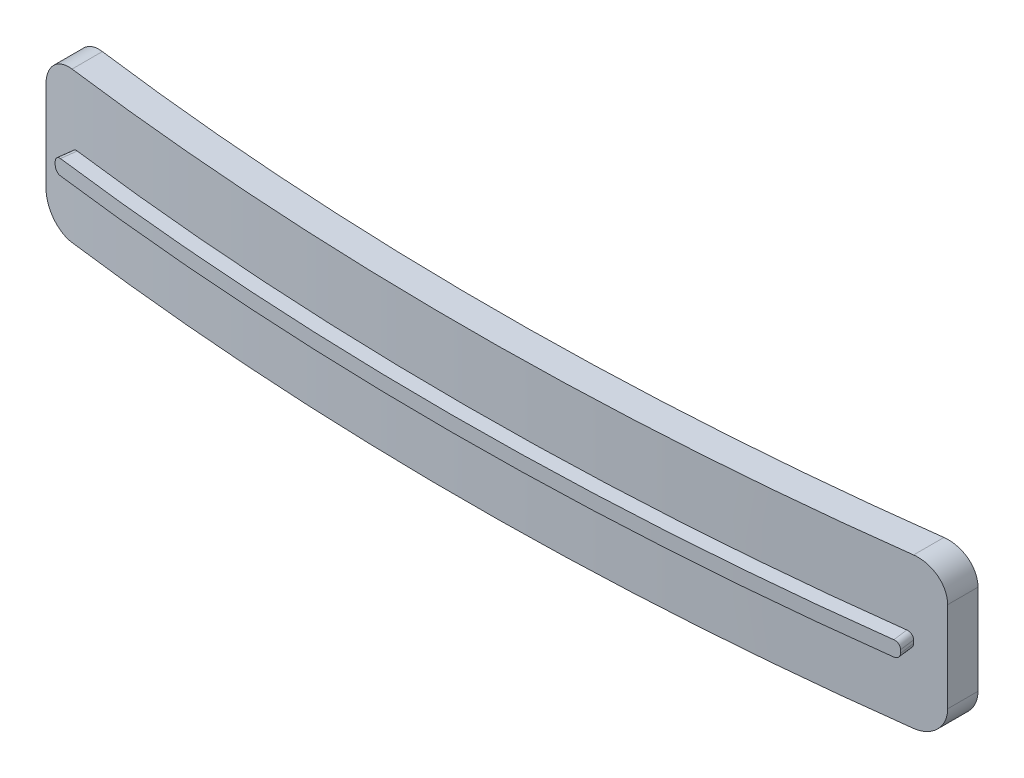
SolidWorks part; units mm, degrees
ref_plane "Front Plane" through (0, 0, 0) normal (0, 0, 1) x (1, 0, 0)
ref_plane "Top Plane" through (0, 0, 0) normal (0, 1, 0) x (1, 0, 0)
ref_plane "Right Plane" through (0, 0, 0) normal (1, 0, 0) x (0, 0, -1)
sketch "Sketch1" plane through (0, 0, 0) normal (0, 1, 0) x (1, 0, 0)
  line L0 (-150, -1076.6007) -> (-150, -1086.6964)
  line L1 (150, -1076.6007) -> (150, -1086.6964)
  arc A0 (-150, -1076.6007) -> (150, -1076.6007) centre (0, 0) ccw
  arc A1 (-150, -1086.6964) -> (150, -1086.6964) centre (0, 0) ccw
  dimension "D1" = 2194
  dimension "D2" = 10
  dimension "D3" = 150
  dimension "D4" = 300
extrude "Boss-Extrude1" add sketch "Sketch1" along normal blind 50
fillet "Fillet1" radius 10 4 edges at (150, 0, 1081.6485) (150, 50, 1081.6485) (-150, 0, 1081.6485) (-150, 50, 1081.6485)
ref_plane "Plane2" through (0, 25, 0) normal (0, 1, 0) x (1, 0, 0)
sketch "Sketch3" plane through (0, 25, 0) normal (0, 1, 0) x (1, 0, 0)
  line L0 (-140, -1088.0299) -> (-140.6381, -1092.989)
  line L1 (140, -1088.0299) -> (140.6381, -1092.989)
  arc A0 (-140, -1088.0299) -> (140, -1088.0299) centre (0, 0) ccw construction
  arc A1 (-140, -1088.0299) -> (140, -1088.0299) centre (0, 0) ccw
  arc A2 (-140.6381, -1092.989) -> (140.6381, -1092.989) centre (0, 0) ccw
  dimension "D1" = 5
extrude "Boss-Extrude2" add sketch "Sketch3" along normal mid plane 5
fillet "Fillet3" radius 2 4 edges at (140.3191, 22.5, 1090.5094) (140.3191, 27.5, 1090.5094) (-140.3191, 22.5, 1090.5094) (-140.3191, 27.5, 1090.5094)
